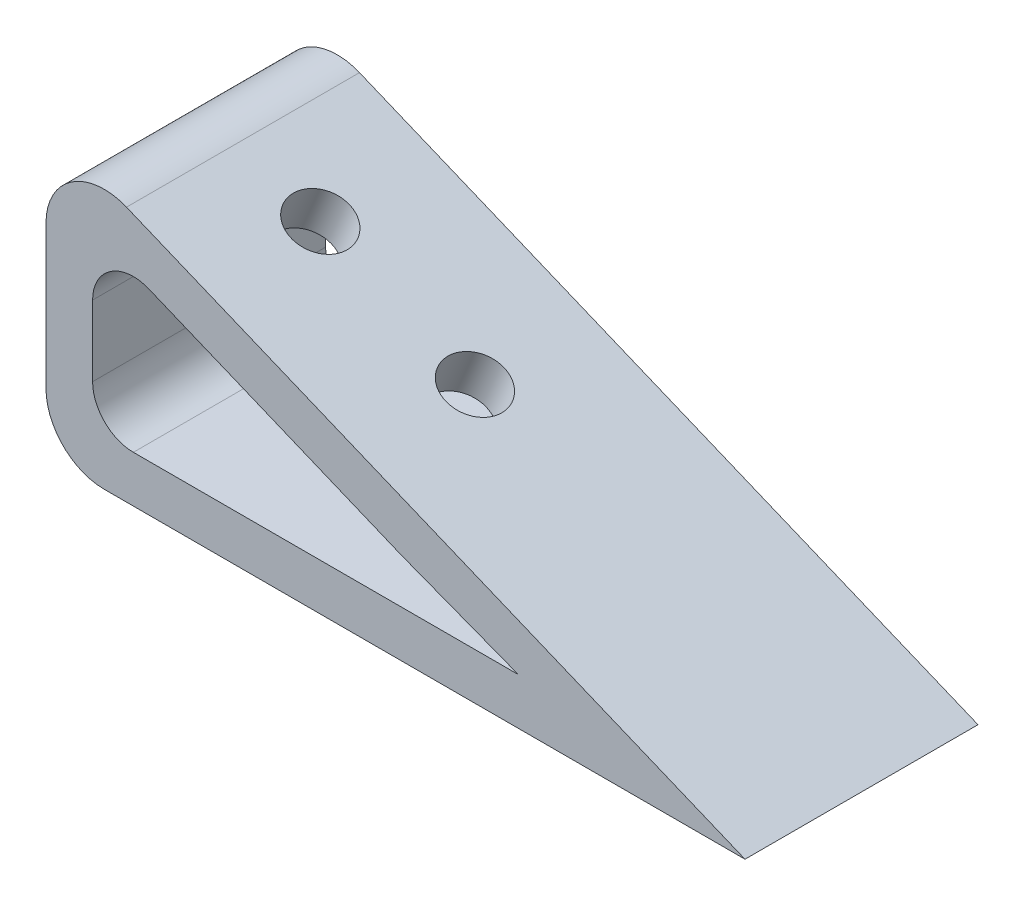
SolidWorks part; units mm, degrees
ref_plane "Front Plane" through (0, 0, 0) normal (0, 0, 1) x (1, 0, 0)
ref_plane "Top Plane" through (0, 0, 0) normal (0, 1, 0) x (1, 0, 0)
ref_plane "Right Plane" through (0, 0, 0) normal (1, 0, 0) x (0, 0, -1)
sketch "Esquisse1" plane through (0, 0, 0) normal (0, 0, 1) x (1, 0, 0)
  line L0 (46.6189, 57.0767) -> (101.6189, 57.0767)
  line L1 (72.1367, 64.9253) -> (50.4549, 73.8799)
  line L2 (94.0854, 57.0767) -> (10.5794, 57.0767) construction
  line L3 (36.2442, 84.0767) -> (108.8827, 54.0767) construction
  line L4 (101.6189, 57.0767) -> (48.5275, 79.0037)
  line L5 (41.6189, 74.3823) -> (41.6189, 62.0767)
  line L6 (45.6189, 70.645) -> (45.6189, 64.5767)
  line L7 (49.1189, 61.0767) -> (71.3732, 61.0767)
  line L8 (81.4551, 61.0767) -> (47.0006, 75.3066) construction
  line L9 (46.6189, 61.0767) -> (81.4551, 61.0767) construction
  line L10 (45.6189, 74.3823) -> (45.6189, 62.0767) construction
  line L11 (71.3732, 61.0767) -> (82.169, 61.0767)
  line L12 (72.1367, 64.9253) -> (82.169, 61.0767)
  arc A0 (48.5275, 79.0037) -> (41.6189, 74.3823) centre (46.6189, 74.3823) ccw
  arc A1 (46.6189, 57.0767) -> (41.6189, 62.0767) centre (46.6189, 62.0767) cw
  arc A6 (46.6189, 61.0767) -> (45.6189, 62.0767) centre (46.6189, 62.0767) cw construction
  arc A8 (47.0006, 75.3066) -> (45.6189, 74.3823) centre (46.6189, 74.3823) ccw construction
  arc A10 (49.1189, 61.0767) -> (45.6189, 64.5767) centre (49.1189, 64.5767) cw
  arc A11 (50.4549, 73.8799) -> (45.6189, 70.645) centre (49.1189, 70.645) ccw
  point P10 (41.6189, 81.857)
  point P13 (41.6189, 57.0767)
  dimension "D2" = 5
  dimension "D3" = 4
  dimension "D5" = 3.5
  dimension "D1" = 60
extrude "Boss.-Extru.1" add sketch "Esquisse1" along normal mid plane 20
sketch "Esquisse2" plane through (34.9456, 84.6131, 0) normal (0.3817, 0.9243, 0) x (0.9243, -0.3817, 0)
  line L0 (14.6948, 0) -> (72.1359, 0) construction
  line L1 (14.6948, -10) -> (14.6948, 10) construction
  line L2 (72.1359, -10) -> (72.1359, 10) construction
  line L3 (43.4153, -10) -> (43.4153, 10) construction
  line L4 (72.1359, -10) -> (14.6948, -10) construction
  line L5 (72.1359, 10) -> (14.6948, 10) construction
  line L6 (29.0553, 10) -> (29.0553, -10) construction
  line L7 (14.6948, 10) -> (29.0553, -10) construction
  line L8 (29.0553, -10) -> (43.4153, 10) construction
  line L9 (43.4153, -10) -> (29.0553, 10) construction
  line L10 (29.0553, 10) -> (14.6948, -10) construction
  circle A0 centre (21.875, 0) radius 2.5
  circle A1 centre (36.2353, 0) radius 2.5
  dimension "D2" = 5
  dimension "D3" = 5
  dimension "D1" = 14.36
extrude "Enlèv. mat.-Extru.1" cut sketch "Esquisse2" against normal blind 8
